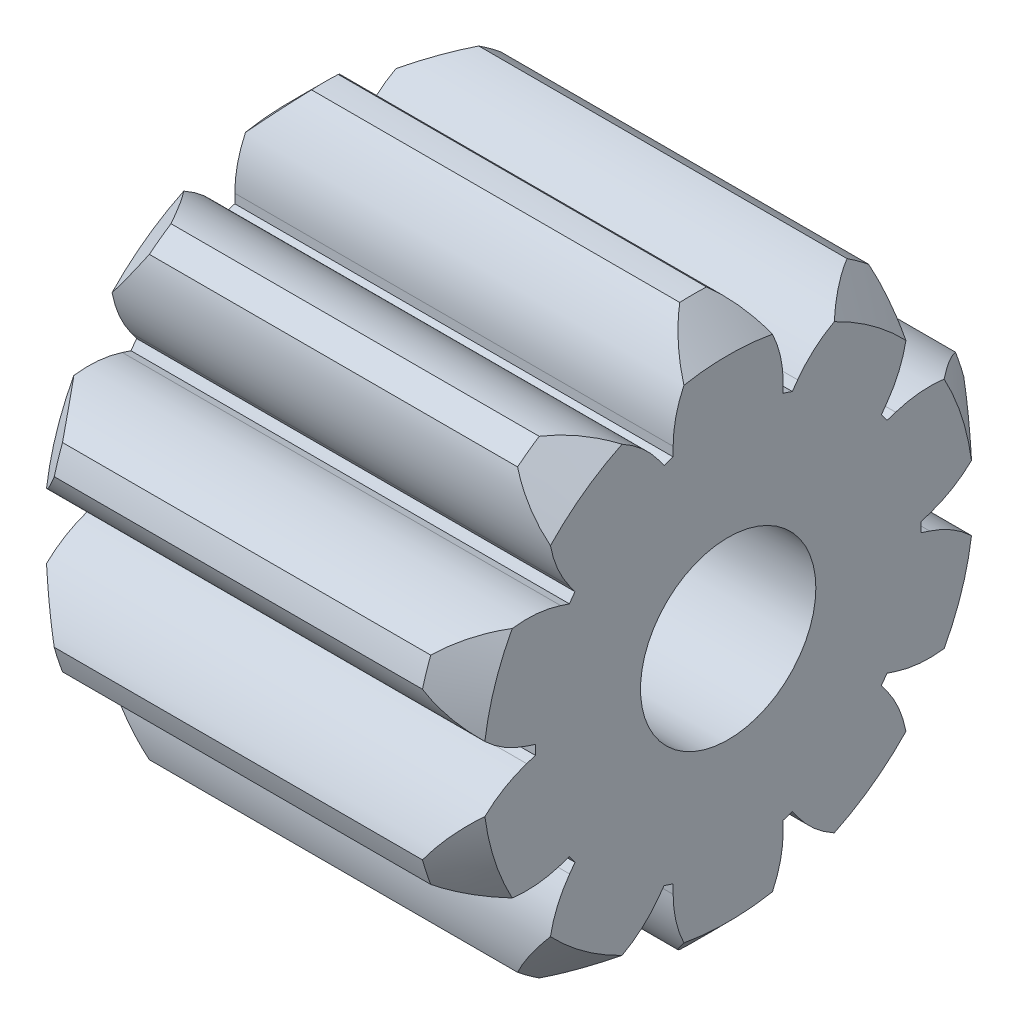
SolidWorks part; units mm, degrees
ref_plane "Front Plane" through (0, 0, 0) normal (0, 0, 1) x (1, 0, 0)
ref_plane "Top Plane" through (0, 0, 0) normal (0, 1, 0) x (1, 0, 0)
ref_plane "Right Plane" through (0, 0, 0) normal (1, 0, 0) x (0, 0, -1)
sketch "Sketch2" plane through (0, 0, 0) normal (1, 0, 0) x (0, 0, -1)
  circle A0 centre (0, 0) radius 2.2
  circle A1 centre (0, 0) radius 1
  dimension "D1" = 4.4
  dimension "D2" = 2
extrude "Boss-Extrude2" add sketch "Sketch2" along normal blind 5
sketch "Sketch3" plane through (0, 0, 0) normal (1, 0, 0) x (0, 0, -1)
  line L0 (-0.6278, 2.2127) -> (-0.6278, 2.1085)
  line L1 (0.6278, 2.2127) -> (0.6278, 2.1085)
  circle A4 centre (0, 0) radius 3.2
  circle A5 centre (0.6278, 2.2127) radius 1.2555
  circle A6 centre (1.6962, 1.5533) radius 1.2555
  circle A7 centre (2.2592, 0.4311) radius 1.2555
  circle A8 centre (-0.6278, 2.2127) radius 1.2555
  circle A9 centre (0, 0) radius 2.3
  circle A10 centre (0, 0) radius 2.2 construction
  circle A11 centre (0, 0) radius 2.2
  point P17 (0, 3.3)
  dimension "D1" = 6.4
  dimension "D2" = 3.3
  dimension "D3" = 4.6
extrude "Boss-Extrude3" add sketch "Sketch3" along normal up to surface (5 mm away) separate body contours A11 L1 A8 | A11 A8 A6 | A11 A6 A9 A5 | A11 A5 L0 | A9 A8 A4 A5
pattern_circular "CirPattern1" count 10 over 360 about axis through (0, 0, 0) along (1, 0, 0) of bodies 103
combine bodies "Combine1" bodies to combine 103 110 109 107 106 102 104 105 108 114 115
sketch "Sketch4" plane through (0, 0, 0) normal (0, 0, 1) x (1, 0, 0)
  line L0 (0, 0) -> (0, 2.8)
  line L1 (0, 2.8) -> (0.4, 3.2)
  line L2 (5, 3.2) -> (0, 3.2) construction
  line L3 (0.4, 3.2) -> (4.6, 3.2)
  line L4 (4.6, 3.2) -> (5, 2.8)
  line L5 (5, 2.8) -> (5, 0)
  line L6 (5, 2.2127) -> (5, 3.1964) construction
  line L8 (0, 0) -> (-1, 0)
  line L9 (-1, 0) -> (-1, 4.2)
  line L10 (-1, 4.2) -> (6, 4.2)
  line L11 (6, 4.2) -> (6, 0)
  line L12 (6, 0) -> (5, 0)
  dimension "D1" = 0.4
  dimension "D2" = 0.4
  dimension "D3" = 0.4
  dimension "D4" = 1
  dimension "D5" = 1
  dimension "D6" = 1
revolve "Cut-Revolve1" cut sketch "Sketch4" angle 360 about L12
